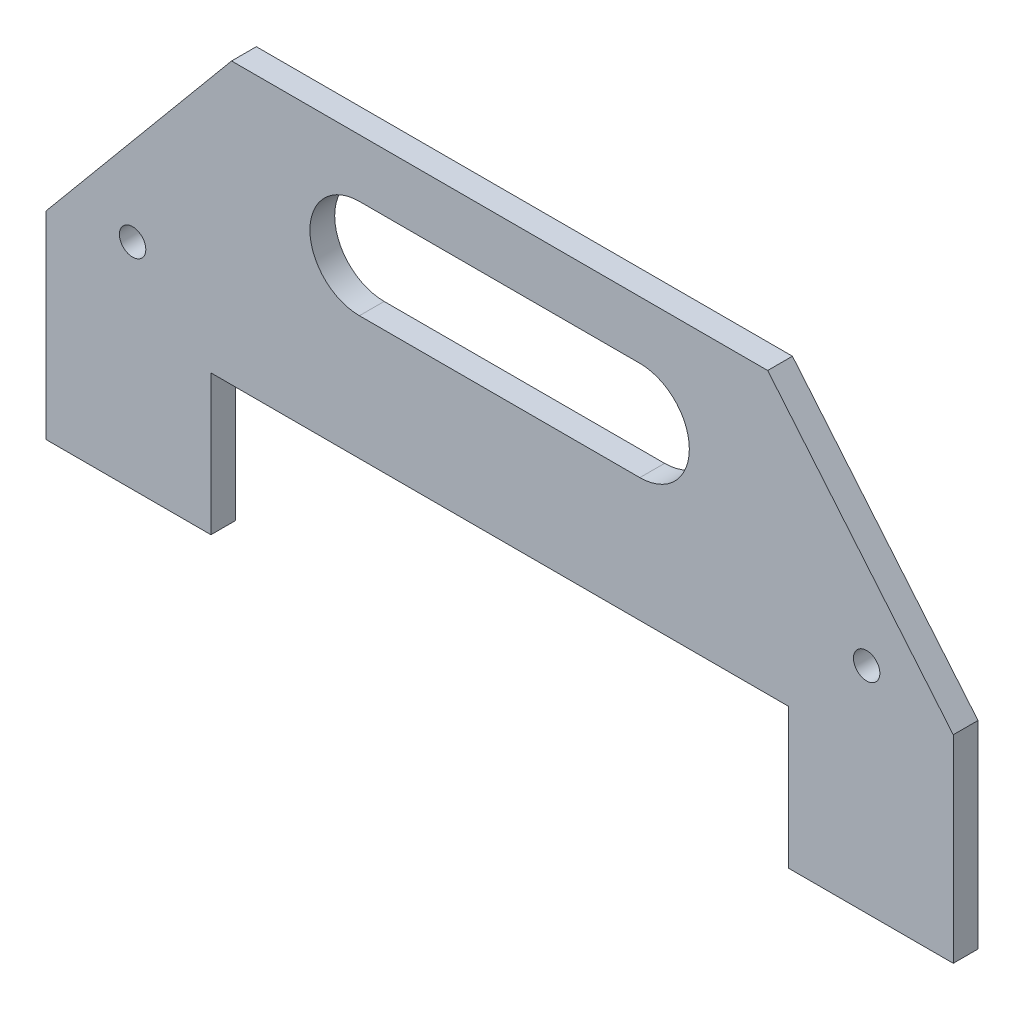
SolidWorks part; units mm, degrees
ref_plane "Alzado" through (0, 0, 0) normal (0, 0, 1) x (1, 0, 0)
ref_plane "Planta" through (0, 0, 0) normal (0, 1, 0) x (1, 0, 0)
ref_plane "Vista lateral" through (0, 0, 0) normal (1, 0, 0) x (0, 0, -1)
sketch "Croquis1" plane through (0, 0, 0) normal (0, 0, 1) x (1, 0, 0)
  line L0 (-55, 0) -> (55, 0)
  line L1 (55, 0) -> (55, 24)
  line L2 (55, 24) -> (32.5, 51)
  line L3 (32.5, 51) -> (-32.5, 51)
  line L4 (-32.5, 51) -> (-55, 24)
  line L5 (-55, 24) -> (-55, 0)
  point P2 (0, 51)
  dimension "D1" = 24
  dimension "D2" = 65
  dimension "D3" = 51
  dimension "D4" = 110
extrude "Saliente-Extruir1" add sketch "Croquis1" along normal blind 3
sketch "Croquis2" plane through (0, 0, 0) normal (0, 0, -1) x (-1, 0, 0)
  line L0 (-53.3333, 26) -> (53.3333, 26) construction
  line L1 (-55, 24) -> (-32.5, 51) construction
  line L2 (32.5, 51) -> (55, 24) construction
  line L3 (-44.5, 51) -> (-44.5, 0) construction
  line L4 (-32.5, 51) -> (32.5, 51) construction
  line L5 (55, 0) -> (-55, 0) construction
  line L6 (44.5, 51) -> (44.5, 0) construction
  line L7 (-55, 0) -> (-55, 24) construction
  line L8 (55, 24) -> (55, 0) construction
  dimension "D1" = 2
  dimension "D2" = 10.5
  dimension "D3" = 10.5
hole_wizard "Taladro de margen para M31" positions "Croquis3D1" profile "Croquis3" hole size "M3" standard "ISO"
sketch3d "Croquis3D1"
  line L0 (44.5, 51, 0) -> (44.5, 0, 0) construction
  line L1 (53.3333, 26, 0) -> (-53.3333, 26, 0) construction
  line L2 (-44.5, 51, 0) -> (-44.5, 0, 0) construction
  point P0 (44.5, 26, 0)
  point P6 (-44.5, 26, 0)
sketch "Croquis3" plane through (44.5, 26, 0) normal (1, 0, 0) x (0, 1, 0)
  line L0 (0, 0) -> (0, 5.9614)
  line L1 (0, 5.9614) -> (1.6, 5)
  line L2 (1.6, 5) -> (1.6, 0)
  line L5 (1.6, 0) -> (0, 0)
  line L10 (0, 5.9614) -> (-1.6, 5) construction
  line L11 (0, -6.35) -> (0, 107.95) construction
  dimension "Diámetro de taladro" = 3.2
  dimension "Profundidad de taladro" = 5
  dimension "Ángulo de perforador" = 118
sketch "Croquis4" plane through (0, 0, 3) normal (0, 0, 1) x (1, 0, 0)
  line L0 (-55, 0) -> (55, 0) construction
  line L1 (-35, 17) -> (35, 17)
  line L2 (-35, 17) -> (-35, 0)
  line L3 (-35, 0) -> (35, 0)
  line L4 (35, 17) -> (35, 0)
  line L6 (55, 0) -> (55, 24) construction
  line L7 (-55, 24) -> (-55, 0) construction
  dimension "D1" = 20
  dimension "D2" = 17
  dimension "D3" = 20
extrude "Cortar-Extruir1" cut sketch "Croquis4" against normal up to next
sketch "Croquis5" plane through (0, 0, 3) normal (0, 0, 1) x (1, 0, 0)
  line L0 (-17, 38) -> (17, 38) construction
  line L1 (-17, 44) -> (17, 44)
  line L2 (-17, 32) -> (17, 32)
  line L3 (32.5, 51) -> (-32.5, 51) construction
  line L4 (35, 17) -> (-35, 17) construction
  arc A0 (-17, 44) -> (-17, 32) centre (-17, 38) ccw
  arc A1 (17, 32) -> (17, 44) centre (17, 38) ccw
  point P2 (0, 38)
  dimension "D1" = 38
  dimension "D2" = 38
  dimension "D3" = 7
  dimension "D4" = 15
extrude "Cortar-Extruir2" cut sketch "Croquis5" against normal up to next
